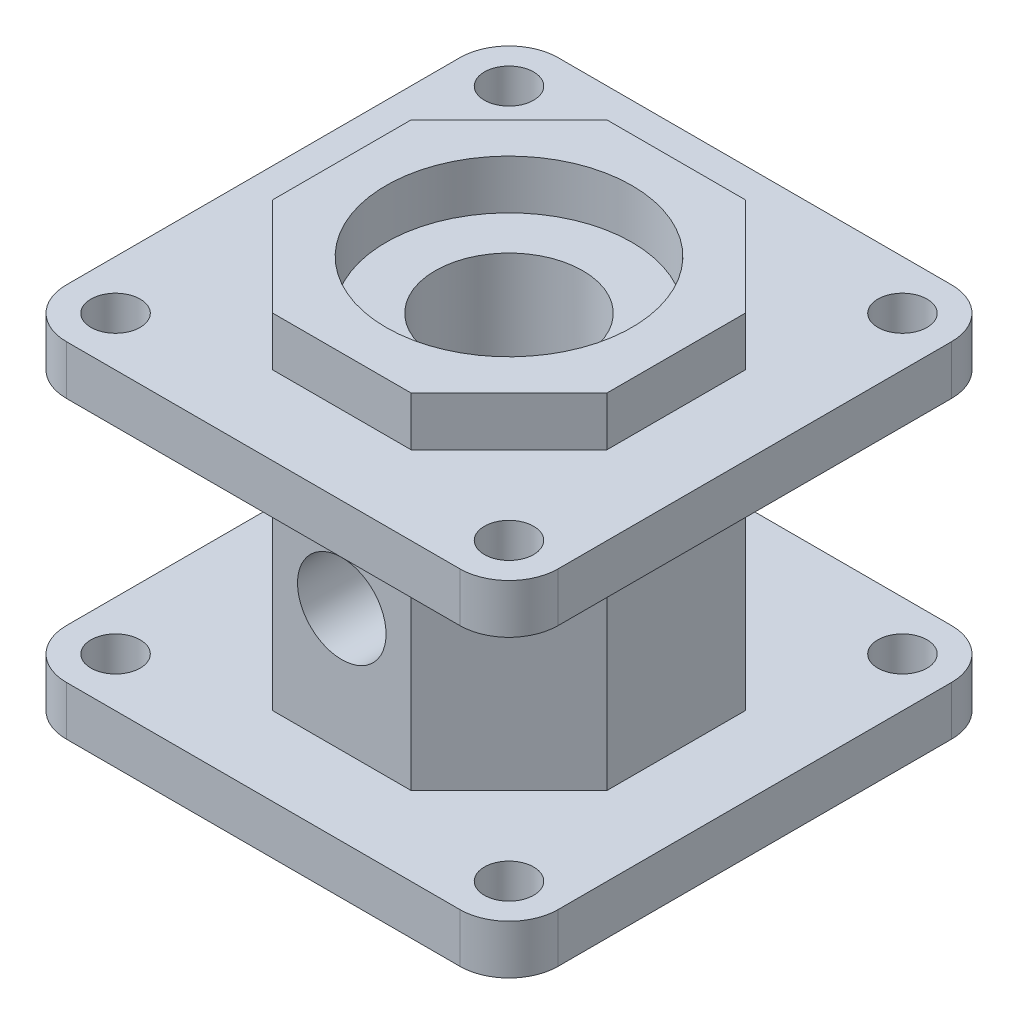
SolidWorks part; units mm, degrees
ref_plane "Front Plane" through (0, 0, 0) normal (0, 0, 1) x (1, 0, 0)
ref_plane "Top Plane" through (0, 0, 0) normal (0, 1, 0) x (1, 0, 0)
ref_plane "Right Plane" through (0, 0, 0) normal (1, 0, 0) x (0, 0, -1)
sketch "Sketch1" plane through (0, 0, 0) normal (0, 1, 0) x (1, 0, 0)
  line L1 (34, 14.0833) -> (14.0833, 34)
  line L2 (14.0833, 34) -> (-14.0833, 34)
  line L3 (-14.0833, 34) -> (-34, 14.0833)
  line L4 (-34, 14.0833) -> (-34, -14.0833)
  line L5 (-34, -14.0833) -> (-14.0833, -34)
  line L6 (-14.0833, -34) -> (14.0833, -34)
  line L7 (14.0833, -34) -> (34, -14.0833)
  line L8 (34, -14.0833) -> (34, 14.0833)
  point P1 (0, 34)
  dimension "D1" = 68
extrude "Boss-Extrude1" add sketch "Sketch1" along normal blind 80
sketch "Sketch2" plane through (0, 80, 0) normal (0, 1, 0) x (1, 0, 0)
  circle A0 centre (0, 0) radius 25
  dimension "D1" = 50
extrude "Cut-Extrude1" cut sketch "Sketch2" against normal blind 10
sketch "Sketch3" plane through (0, 0, 0) normal (0, -1, 0) x (1, 0, 0)
  circle A0 centre (0, 0) radius 15
  dimension "D1" = 30
extrude "Cut-Extrude2" cut sketch "Sketch3" against normal blind 70
sketch "Sketch4" plane through (0, 0, 0) normal (0, -1, 0) x (1, 0, 0)
  line L0 (34, 14.0833) -> (34, -14.0833) construction
  line L1 (-40, 50) -> (40, 50)
  line L2 (-50, 40) -> (-50, -40)
  line L3 (-40, -50) -> (40, -50)
  line L4 (50, 40) -> (50, -40)
  arc A0 (-40, -50) -> (-50, -40) centre (-40, -40) cw
  arc A1 (40, -50) -> (50, -40) centre (40, -40) ccw
  arc A2 (50, 40) -> (40, 50) centre (40, 40) ccw
  arc A3 (-50, 40) -> (-40, 50) centre (-40, 40) cw
  circle A4 centre (-40, 40) radius 5
  circle A5 centre (40, 40) radius 5
  circle A6 centre (-40, -40) radius 5
  circle A7 centre (40, -40) radius 5
  point P0 (0, 0)
  dimension "D3" = 10
  dimension "D2" = 100
  dimension "D4" = 10
  dimension "D1" = 100
extrude "Boss-Extrude2" add sketch "Sketch4" against normal blind 10
ref_plane "Plane1" through (0, 60, 0) normal (0, -1, 0) x (-1, 0, 0)
sketch "Sketch5" plane through (0, 60, 0) normal (0, -1, 0) x (-1, 0, 0)
  line L1 (-40, 50) -> (40, 50)
  line L2 (-50, 40) -> (-50, -40)
  line L3 (-40, -50) -> (40, -50)
  line L4 (50, 40) -> (50, -40)
  line L5 (-50, 50) -> (50, -50) construction
  line L6 (-50, -50) -> (50, 50) construction
  arc A0 (50, 40) -> (40, 50) centre (40, 40) ccw
  arc A1 (40, -50) -> (50, -40) centre (40, -40) ccw
  arc A2 (-40, -50) -> (-50, -40) centre (-40, -40) cw
  arc A3 (-50, 40) -> (-40, 50) centre (-40, 40) cw
  circle A4 centre (-40, 40) radius 5
  circle A5 centre (40, 40) radius 5
  circle A6 centre (-40, -40) radius 5
  circle A7 centre (40, -40) radius 5
  point P0 (0, 0)
  dimension "D3" = 10
  dimension "D1" = 100
  dimension "D2" = 100
extrude "Boss-Extrude3" add sketch "Sketch5" against normal blind 10
sketch "Sketch6" plane through (0, 0, 0) normal (0, -1, 0) x (1, 0, 0)
  circle A0 centre (0, 0) radius 15
  dimension "D1" = 30
extrude "Cut-Extrude3" cut sketch "Sketch6" against normal blind 80
sketch "Sketch7" plane through (0, 0, 34) normal (0, 0, 1) x (1, 0, 0)
  circle A0 centre (0, 35) radius 9
  dimension "D2" = 18
  dimension "D1" = 35
extrude "Cut-Extrude4" cut sketch "Sketch7" against normal blind 80
